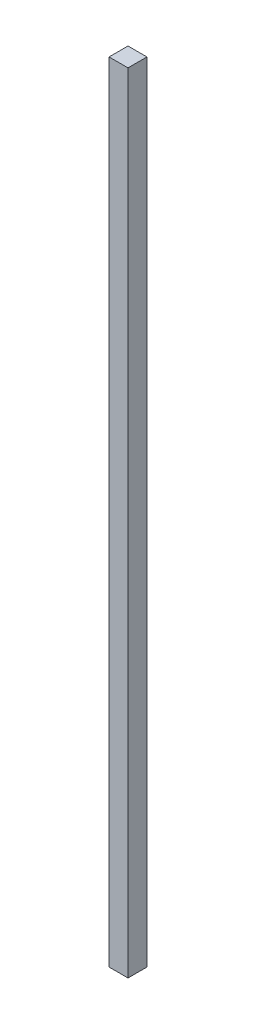
SolidWorks part; units mm, degrees
ref_plane "Front Plane" through (0, 0, 0) normal (0, 0, 1) x (1, 0, 0)
ref_plane "Top Plane" through (0, 0, 0) normal (0, 1, 0) x (1, 0, 0)
ref_plane "Right Plane" through (0, 0, 0) normal (1, 0, 0) x (0, 0, -1)
sketch "Sketch1" plane through (0, 0, 0) normal (0, 1, 0) x (1, 0, 0)
  line L1 (-3, 3) -> (3, 3)
  line L2 (-3, 3) -> (-3, -3)
  line L3 (-3, -3) -> (3, -3)
  line L4 (3, 3) -> (3, -3)
  line L5 (-3, 3) -> (3, -3) construction
  line L6 (-3, -3) -> (3, 3) construction
  point P0 (0, 0)
  dimension "D1" = 6
  dimension "D2" = 6
extrude "Boss-Extrude1" add sketch "Sketch1" along normal mid plane 250
